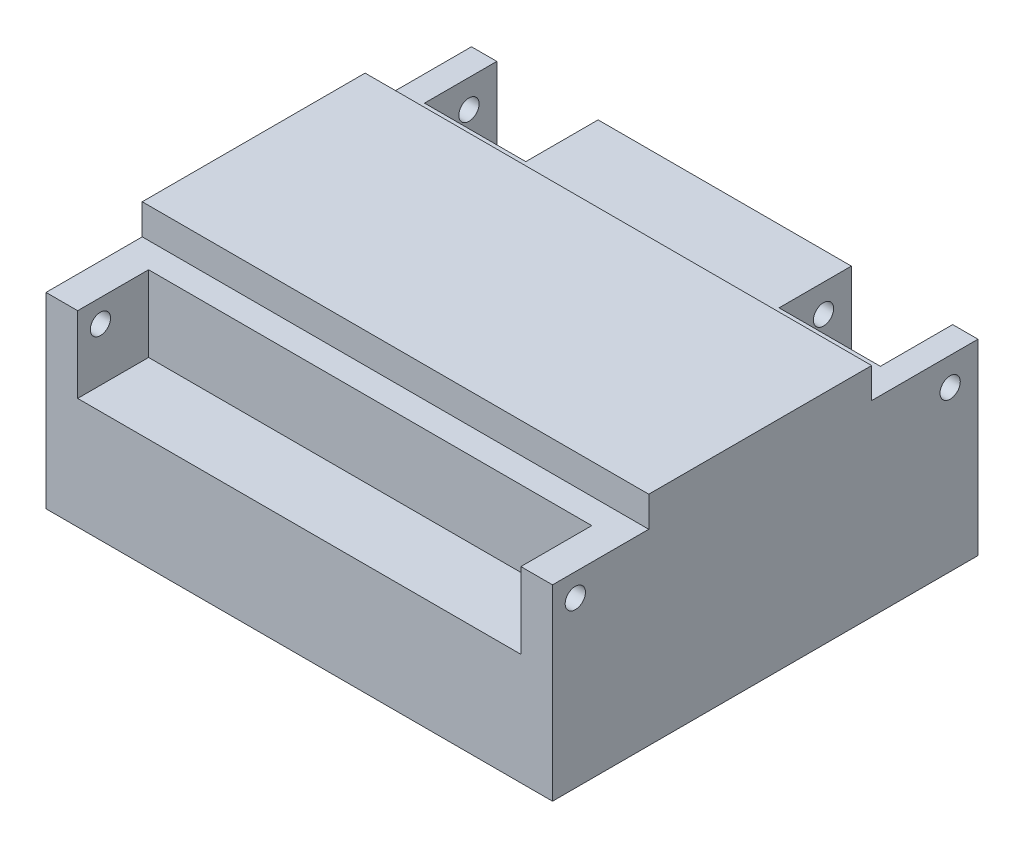
SolidWorks part; units mm, degrees
ref_plane "Front Plane" through (0, 0, 0) normal (0, 0, 1) x (1, 0, 0)
ref_plane "Top Plane" through (0, 0, 0) normal (0, 1, 0) x (1, 0, 0)
ref_plane "Right Plane" through (0, 0, 0) normal (1, 0, 0) x (0, 0, -1)
sketch "Sketch1" plane through (0, 0, 0) normal (0, 1, 0) x (1, 0, 0)
  line L1 (-50, 42) -> (50, 42)
  line L2 (-50, 42) -> (-50, -42)
  line L3 (-50, -42) -> (50, -42)
  line L4 (50, 42) -> (50, -42)
  line L5 (-50, 42) -> (50, -42) construction
  line L6 (-50, -42) -> (50, 42) construction
  point P0 (0, 0)
extrude "Boss-Extrude1" add sketch "Sketch1" along normal blind 6
sketch "Sketch2" plane through (0, 6, 0) normal (0, 1, 0) x (1, 0, 0)
  line L0 (50, -42) -> (50, 42) construction
  line L1 (-50, 21) -> (50, 21)
  line L2 (-50, 21) -> (-50, -23)
  line L3 (-50, -23) -> (50, -23)
  line L4 (50, 21) -> (50, -23)
  line L5 (-50, 21) -> (50, -23) construction
  line L6 (-50, -23) -> (50, 21) construction
  line L7 (50, 42) -> (-50, 42) construction
  point P0 (0, -1)
  dimension "D1" = 21
extrude "Boss-Extrude2" add sketch "Sketch2" along normal blind 6
sketch "Sketch3" plane through (0, 0, 0) normal (0, -1, 0) x (1, 0, 0)
  line L1 (-50, 42) -> (50, 42)
  line L2 (-50, 42) -> (-50, -42)
  line L3 (-50, -42) -> (50, -42)
  line L4 (50, 42) -> (50, -42)
extrude "Boss-Extrude3" add sketch "Sketch3" along normal blind 31
sketch "Sketch4" plane through (0, 0, -42) normal (0, 0, -1) x (-1, 0, 0)
  line L0 (-54.2554, 0) -> (-29.4687, 0) construction
  line L1 (-50, 6) -> (50, 6) construction
  line L3 (-15, 0) -> (15, 0)
  line L4 (-15, 0) -> (-15, -5.6994)
  line L5 (-15, -5.6994) -> (15, -5.6994)
  line L6 (15, 0) -> (15, -5.6994)
  dimension "D1" = 6
  dimension "D2" = 15
  dimension "D3" = 15
extrude "Cut-Extrude1" cut sketch "Sketch4" against normal blind 30
sketch "Sketch5" plane through (-50, 0, 0) normal (-1, 0, 0) x (0, 0, 1)
  line L0 (42, 6) -> (42, -31) construction
  line L1 (23, 6) -> (42, 6) construction
  circle A0 centre (37.5, 1.5) radius 2
  dimension "D1" = 4.5
  dimension "D2" = 4.5
extrude "Cut-Extrude2" cut sketch "Sketch5" against normal through all
sketch "Sketch6" plane through (0, 6, 0) normal (0, 1, 0) x (1, 0, 0)
  line L0 (-50, -23) -> (-50, -42) construction
  line L1 (-43.75, -54) -> (43.75, -54)
  line L2 (-43.75, -54) -> (-43.75, -28)
  line L3 (-43.75, -28) -> (43.75, -28)
  line L4 (43.75, -54) -> (43.75, -28)
  dimension "D1" = 6.25
extrude "Cut-Extrude3" cut sketch "Sketch6" against normal blind 15
sketch "Sketch7" plane through (50, 0, 0) normal (1, 0, 0) x (0, 0, -1)
  line L0 (42, 6) -> (42, -31) construction
  line L1 (21, 6) -> (42, 6) construction
  circle A0 centre (36.5, 0.5) radius 2
  dimension "D1" = 5.5
  dimension "D2" = 5.5
extrude "Cut-Extrude4" cut sketch "Sketch7" against normal through all
sketch "Sketch8" plane through (0, 6, 0) normal (0, 1, 0) x (1, 0, 0)
  line L0 (50, 42) -> (-50, 42) construction
  line L1 (-45, 42) -> (-25, 42)
  line L2 (-45, 42) -> (-45, 27.723)
  line L3 (-45, 27.723) -> (-25, 27.723)
  line L4 (-25, 42) -> (-25, 27.723)
  line L5 (-45, -30) -> (-45, 14.1908) construction
  line L6 (0, 42) -> (0, -20.0588) construction
  line L7 (25, 42) -> (25, 27.723)
  line L8 (45, 27.723) -> (25, 27.723)
  line L9 (45, 42) -> (45, 27.723)
  line L10 (45, 42) -> (25, 42)
extrude "Cut-Extrude5" cut sketch "Sketch8" against normal blind 15
